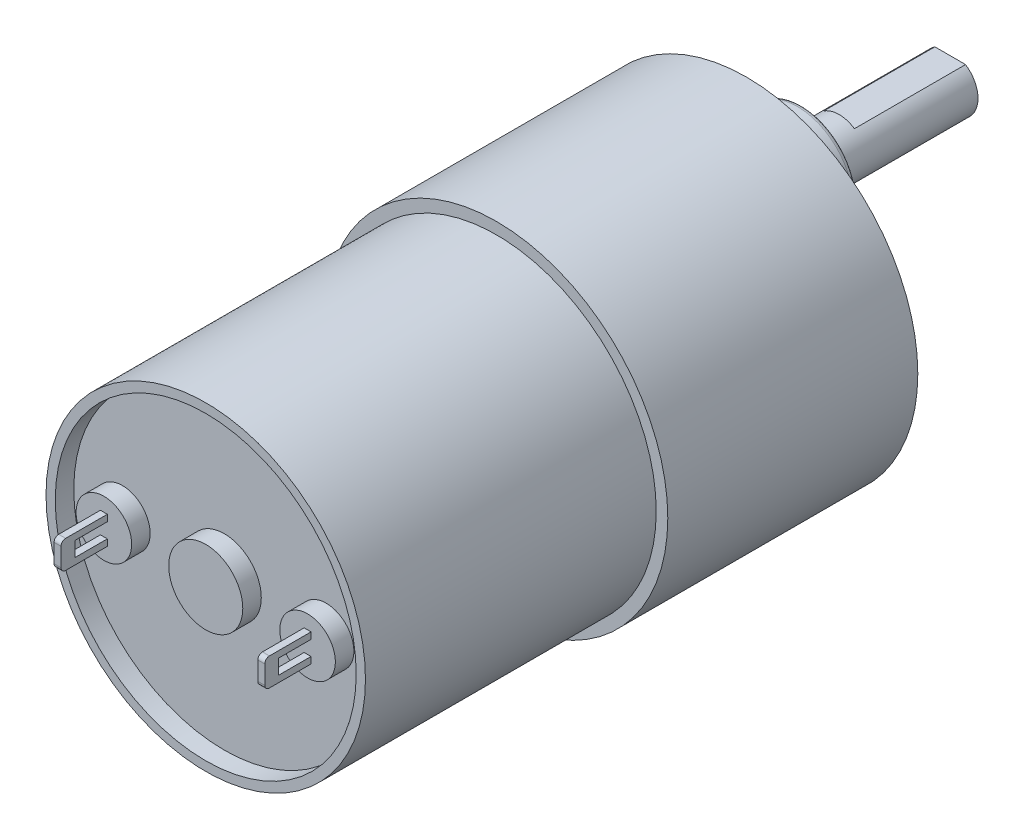
SolidWorks part; units mm, degrees
ref_plane "Alzado" through (0, 0, 0) normal (0, 0, 1) x (1, 0, 0)
ref_plane "Planta" through (0, 0, 0) normal (0, 1, 0) x (1, 0, 0)
ref_plane "Vista lateral" through (0, 0, 0) normal (1, 0, 0) x (0, 0, -1)
sketch "Croquis1" plane through (0, 0, 0) normal (0, 0, 1) x (1, 0, 0)
  circle A0 centre (0, 0) radius 17.25
  dimension "D1" = 34.5
extrude "Saliente-Extruir1" add sketch "Croquis1" along normal blind 31.4
sketch "Croquis2" plane through (0, 0, 0) normal (0, 0, -1) x (-1, 0, 0)
  circle A0 centre (0, 0) radius 18.5
  dimension "D1" = 37
extrude "Saliente-Extruir2" add sketch "Croquis2" along normal blind 27
sketch "Croquis3" plane through (0, 0, -27) normal (0, 0, -1) x (-1, 0, 0)
  circle A0 centre (0, 7) radius 6
  circle A2 centre (0, 0) radius 18.5 construction
  point P5 (0, 1)
  point P6 (0, 18.5)
  point P7 (0, 7)
  point P8 (0, 18.5)
  dimension "D1" = 12
  dimension "D2" = 17.5
extrude "Saliente-Extruir3" add sketch "Croquis3" along normal blind 6
sketch "Croquis4" plane through (0, 0, -33) normal (0, 0, -1) x (-1, 0, 0)
  circle A0 centre (0, 7) radius 3
  dimension "D1" = 6
extrude "Saliente-Extruir4" add sketch "Croquis4" along normal blind 16
sketch "Croquis5" plane through (0, 0, -49) normal (0, 0, -1) x (-1, 0, 0)
  line L0 (-1.6583, 9.5) -> (1.6583, 9.5)
  line L1 (0, 4) -> (0, 9.5) construction
  circle A0 centre (0, 7) radius 3 construction
  circle A1 centre (0, 7) radius 3 construction
  arc A2 (1.6583, 9.5) -> (-1.6583, 9.5) centre (0, 7) ccw
  dimension "D1" = 5.5
extrude "Cortar-Extruir1" cut sketch "Croquis5" against normal blind 12
sketch "Croquis8" plane through (0, 0, 31.4) normal (0, 0, 1) x (1, 0, 0)
  circle A1 centre (0, 0) radius 4
  circle A2 centre (0, 0) radius 16.25
  circle A3 centre (0, 0) radius 16.25
  dimension "D2" = 8
  dimension "D1" = 1
extrude "Cortar-Extruir2" cut sketch "Croquis8" against normal blind 2
sketch "Croquis9" plane through (0, 0, 29.4) normal (0, 0, 1) x (1, 0, 0)
  circle A0 centre (-11, 0) radius 3
  circle A1 centre (11, 0) radius 3
  point P4 (0, 0)
  dimension "D1" = 6
  dimension "D2" = 11
  dimension "D3" = 11
extrude "Saliente-Extruir5" add sketch "Croquis9" along normal blind 2 separate body
sketch "Croquis10" plane through (0, 0, 31.4) normal (0, 0, 1) x (1, 0, 0)
  line L0 (0, 0) -> (0, -4) construction
  line L1 (-10.625, 1.5) -> (-11.375, 1.5)
  line L2 (-10.625, 1.5) -> (-10.625, -1.5)
  line L3 (-10.625, -1.5) -> (-11.375, -1.5)
  line L4 (-11.375, 1.5) -> (-11.375, -1.5)
  line L5 (-10.625, 1.5) -> (-11.375, -1.5) construction
  line L6 (-10.625, -1.5) -> (-11.375, 1.5) construction
  line L7 (10.625, -1.5) -> (11.375, -1.5)
  line L8 (11.375, 1.5) -> (11.375, -1.5)
  line L9 (10.625, 1.5) -> (11.375, 1.5)
  line L10 (10.625, 1.5) -> (10.625, -1.5)
  circle A0 centre (0, 0) radius 4 construction
  point P0 (-11, 0)
  dimension "D1" = 0.75
  dimension "D2" = 3
extrude "Saliente-Extruir6" add sketch "Croquis10" along normal blind 5 separate body
sketch "Croquis11" plane through (-11.375, 0, 0) normal (-1, 0, 0) x (0, 0, 1)
  line L0 (31.4, 1.5) -> (31.4, -1.5) construction
  line L1 (31.4, 0.8) -> (34.9, 0.8)
  line L2 (31.4, 0.8) -> (31.4, -0.8)
  line L3 (31.4, -0.8) -> (34.9, -0.8)
  line L4 (34.9, 0.8) -> (34.9, -0.8)
  line L5 (36.4, 1.5) -> (36.4, -1.5) construction
  line L6 (36.4, 1.5) -> (31.4, 1.5) construction
  point P6 (34.9, 0)
  point P9 (36.4, 0)
  dimension "D1" = 0.7
  dimension "D2" = 1.5
extrude "Cortar-Extruir3" cut sketch "Croquis11" against normal up to surface (22.75 mm away)
fillet "Redondeo1" radius 0.5 2 edges at (-11, 1.5, 36.4) (-11, -1.5, 36.4)
fillet "Redondeo2" radius 0.5 2 edges at (11, -1.5, 36.4) (11, 1.5, 36.4)
fillet "Redondeo3" radius 0.5 1 edges at (-6, 7, -33)
sketch "Croquis12" plane through (0, 0, -27) normal (0, 0, -1) x (-1, 0, 0)
  line L0 (0, 0) -> (-15.5, 0) construction
  circle A0 centre (0, 0) radius 15.5 construction
  circle A1 centre (-15.5, 0) radius 1.5
  circle A2 centre (-7.75, 13.4234) radius 1.5
  circle A3 centre (7.75, 13.4234) radius 1.5
  circle A4 centre (15.5, 0) radius 1.5
  circle A5 centre (7.75, -13.4234) radius 1.5
  circle A6 centre (-7.75, -13.4234) radius 1.5
  point P6 (-5.1106, 11.5026)
  dimension "D1" = 31
  dimension "D2" = 3
  dimension "D4" = 15.5
  dimension "D3" = 6
extrude "Cortar-Extruir4" cut sketch "Croquis12" against normal blind 3
